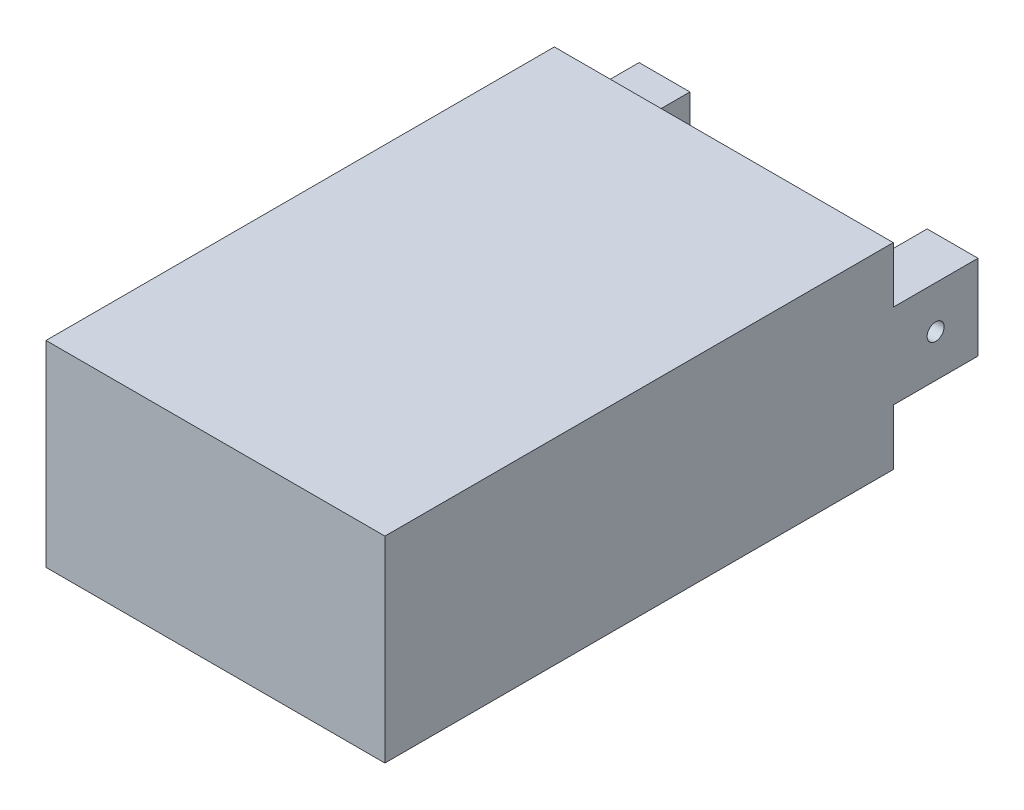
SolidWorks part; units mm, degrees
material "Balsa"
ref_plane "Front Plane" through (0, 0, 0) normal (0, 0, 1) x (1, 0, 0)
ref_plane "Top Plane" through (0, 0, 0) normal (0, 1, 0) x (1, 0, 0)
ref_plane "Right Plane" through (0, 0, 0) normal (1, 0, 0) x (0, 0, -1)
sketch "Sketch2" plane through (0, 0, 0) normal (0, 0, 1) x (1, 0, 0)
  line L1 (50, -29) -> (-50, -29)
  line L2 (50, -29) -> (50, 29)
  line L3 (50, 29) -> (-50, 29)
  line L4 (-50, -29) -> (-50, 29)
  line L5 (50, -29) -> (-50, 29) construction
  line L6 (50, 29) -> (-50, -29) construction
  point P0 (0, 0)
  dimension "D1" = 100
  dimension "D2" = 58
extrude "Boss-Extrude1" add sketch "Sketch2" along normal blind 150
sketch "Sketch3" plane through (0, 0, 0) normal (0, 0, -1) x (-1, 0, 0)
  line L0 (50, -12.5) -> (35, -12.5)
  line L1 (50, 29) -> (50, -29) construction
  line L2 (35, -12.5) -> (35, 12.5)
  line L3 (35, 12.5) -> (50, 12.5)
  line L4 (0, 0) -> (0, 48.1725) construction
  line L5 (-50, -12.5) -> (-35, -12.5)
  line L6 (-35, -12.5) -> (-35, 12.5)
  line L7 (-35, 12.5) -> (-50, 12.5)
  line L8 (0, 0) -> (17.3159, 0) construction
  line L9 (50, 12.5) -> (50, -12.5)
  line L10 (-50, 12.5) -> (-50, -12.5)
  dimension "D1" = 25
  dimension "D2" = 15
extrude "Boss-Extrude2" add sketch "Sketch3" along normal blind 25
sketch "Sketch4" plane through (-50, 0, 0) normal (-1, 0, 0) x (0, 0, 1)
  line L0 (0, -12.5) -> (0, -29) construction
  circle A0 centre (-12.5, 0) radius 2.5
  dimension "D1" = 5
  dimension "D2" = 12.5
extrude "Cut-Extrude1" cut sketch "Sketch4" against normal up to surface (100 mm away) up to face at (50, 0, 31.25)
